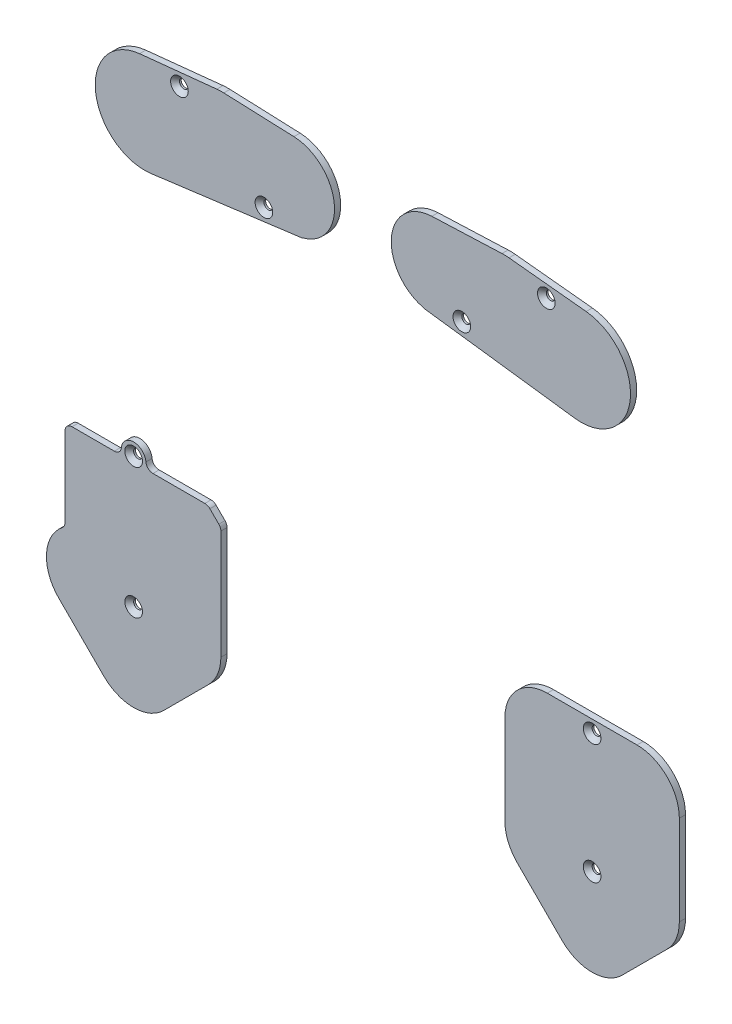
SolidWorks part; units mm, degrees
ref_plane "Front Plane" through (0, 0, 0) normal (0, 0, 1) x (1, 0, 0)
ref_plane "Top Plane" through (0, 0, 0) normal (0, 1, 0) x (1, 0, 0)
ref_plane "Right Plane" through (0, 0, 0) normal (1, 0, 0) x (0, 0, -1)
sketch "Sketch1" plane through (0, 0, 0) normal (0, 0, 1) x (1, 0, 0)
  line L0 (-43.969, -24.5) -> (-40.2721, -28.1969)
  line L2 (-40.2721, -28.1969) -> (-40.2721, -60)
  line L5 (63.3122, 76.6851) -> (41.4267, 78.9271)
  line L6 (39.439, 78.9888) -> (19.5552, 78.1913)
  line L7 (89.7279, -60) -> (89.7279, -34.5442)
  line L8 (77.7279, -22.5442) -> (52.2721, -22.5442)
  line L9 (40.2721, -34.5442) -> (40.2721, -60)
  line L10 (43.7868, -68.4853) -> (56.5147, -81.2132)
  line L11 (73.4853, -81.2132) -> (86.2132, -68.4853)
  line L12 (89.7279, -60) -> (89.7279, -34.5442)
  line L13 (-70.4772, -24.5) -> (-82.469, -24.5)
  line L14 (-84.469, -26.5) -> (-84.469, -49.0641)
  line L15 (-86.2132, -68.4853) -> (-73.4853, -81.2132)
  line L16 (-56.5147, -81.2132) -> (-43.7868, -68.4853)
  line L17 (-40.2721, -60) -> (-40.2721, -50)
  line L18 (-40.2721, -50) -> (-42.2721, -50)
  line L19 (-42.2721, -50) -> (-42.2721, -60)
  line L20 (-45.201, -67.0711) -> (-57.9289, -79.799)
  line L21 (-72.0711, -79.799) -> (-84.799, -67.0711)
  line L22 (-82.469, -51.1953) -> (-82.469, -26.5)
  line L23 (-82.469, -26.5) -> (-43.969, -26.5)
  line L24 (-43.969, -26.5) -> (-43.969, -24.5)
  line L25 (-43.969, -24.5) -> (-59.5228, -24.5)
  line L26 (-70.4772, -24.5) -> (-82.469, -24.5)
  line L27 (-84.469, -26.5) -> (-84.469, -49.0641)
  line L28 (-86.2132, -68.4853) -> (-73.4853, -81.2132)
  line L29 (-56.5147, -81.2132) -> (-43.7868, -68.4853)
  line L38 (-43.969, -24.5) -> (-59.5228, -24.5)
  line L39 (77.7279, -22.5442) -> (52.2721, -22.5442)
  line L40 (40.2721, -34.5442) -> (40.2721, -60)
  line L41 (43.7868, -68.4853) -> (56.5147, -81.2132)
  line L42 (73.4853, -81.2132) -> (86.2132, -68.4853)
  line L43 (17.3834, 54.4454) -> (60.0743, 48.8756)
  line L44 (63.3122, 76.6851) -> (41.4267, 78.9271)
  line L45 (39.439, 78.9888) -> (19.5552, 78.1913)
  line L46 (17.3834, 54.4454) -> (60.0743, 48.8756)
  line L47 (-41.4267, 78.9271) -> (-63.3122, 76.6851)
  line L48 (-60.0743, 48.8756) -> (-17.3834, 54.4454)
  line L49 (-19.5552, 78.1913) -> (-39.439, 78.9888)
  line L50 (-41.4267, 78.9271) -> (-63.3122, 76.6851)
  line L51 (-60.0743, 48.8756) -> (-17.3834, 54.4454)
  line L52 (-19.5552, 78.1913) -> (-39.439, 78.9888)
  circle A0 centre (-52.0128, 74.3243) radius 1.5 construction
  circle A1 centre (-52.0128, 74.3243) radius 1.5
  circle A2 centre (-28.0593, 56.5822) radius 1.5 construction
  circle A3 centre (-28.0593, 56.5822) radius 1.5
  arc A4 (60.0743, 48.8756) -> (63.3122, 76.6851) centre (61.8855, 62.758) ccw
  arc A5 (86.2132, -68.4853) -> (89.7279, -60) centre (77.7279, -60) ccw
  arc A6 (89.7279, -34.5442) -> (77.7279, -22.5442) centre (77.7279, -34.5442) ccw
  arc A7 (52.2721, -22.5442) -> (40.2721, -34.5442) centre (52.2721, -34.5442) ccw
  arc A8 (40.2721, -60) -> (43.7868, -68.4853) centre (52.2721, -60) ccw
  arc A9 (56.5147, -81.2132) -> (73.4853, -81.2132) centre (65, -72.7279) ccw
  arc A10 (86.2132, -68.4853) -> (89.7279, -60) centre (77.7279, -60) ccw
  arc A11 (-82.469, -24.5) -> (-84.469, -26.5) centre (-82.469, -26.5) ccw
  arc A12 (-85.2203, -50.6264) -> (-84.469, -49.0641) centre (-86.469, -49.0641) ccw
  arc A13 (-85.2203, -50.6264) -> (-86.2132, -68.4853) centre (-77.7279, -60) ccw
  arc A14 (-73.4853, -81.2132) -> (-56.5147, -81.2132) centre (-65, -72.7279) ccw
  arc A15 (-43.7868, -68.4853) -> (-40.2721, -60) centre (-52.2721, -60) ccw
  arc A16 (-45.201, -67.0711) -> (-42.2721, -60) centre (-52.2721, -60) ccw
  arc A17 (-72.0711, -79.799) -> (-57.9289, -79.799) centre (-65, -72.7279) ccw
  arc A18 (-82.469, -51.1953) -> (-84.799, -67.0711) centre (-77.7279, -60) ccw
  arc A19 (-61.5145, -22.6818) -> (-59.5228, -24.5) centre (-59.5228, -22.5) ccw
  arc A20 (-61.5145, -22.6818) -> (-68.4855, -22.6818) centre (-65, -23) ccw
  arc A21 (-70.4772, -24.5) -> (-68.4855, -22.6818) centre (-70.4772, -22.5) ccw
  arc A22 (-82.469, -24.5) -> (-84.469, -26.5) centre (-82.469, -26.5) ccw
  arc A23 (-85.2203, -50.6264) -> (-84.469, -49.0641) centre (-86.469, -49.0641) ccw
  arc A24 (-85.2203, -50.6264) -> (-86.2132, -68.4853) centre (-77.7279, -60) ccw
  arc A25 (-73.4853, -81.2132) -> (-56.5147, -81.2132) centre (-65, -72.7279) ccw
  arc A26 (-43.7868, -68.4853) -> (-40.2721, -60) centre (-52.2721, -60) ccw
  arc A30 (-61.5145, -22.6818) -> (-59.5228, -24.5) centre (-59.5228, -22.5) ccw
  arc A31 (-61.5145, -22.6818) -> (-68.4855, -22.6818) centre (-65, -23) ccw
  arc A32 (-70.4772, -24.5) -> (-68.4855, -22.6818) centre (-70.4772, -22.5) ccw
  arc A33 (89.7279, -34.5442) -> (77.7279, -22.5442) centre (77.7279, -34.5442) ccw
  arc A34 (52.2721, -22.5442) -> (40.2721, -34.5442) centre (52.2721, -34.5442) ccw
  arc A35 (40.2721, -60) -> (43.7868, -68.4853) centre (52.2721, -60) ccw
  arc A36 (56.5147, -81.2132) -> (73.4853, -81.2132) centre (65, -72.7279) ccw
  arc A37 (41.4267, 78.9271) -> (39.439, 78.9888) centre (40, 65) ccw
  arc A38 (19.5552, 78.1913) -> (16.9911, 54.5937) centre (20.0361, 66.201) ccw
  arc A39 (17.3834, 54.4454) -> (16.9911, 54.5937) centre (16.4837, 52.6592) ccw
  arc A40 (60.0743, 48.8756) -> (63.3122, 76.6851) centre (61.8855, 62.758) ccw
  arc A41 (41.4267, 78.9271) -> (39.439, 78.9888) centre (40, 65) ccw
  arc A42 (19.5552, 78.1913) -> (16.9911, 54.5937) centre (20.0361, 66.201) ccw
  arc A43 (17.3834, 54.4454) -> (16.9911, 54.5937) centre (16.4837, 52.6592) ccw
  arc A44 (-39.439, 78.9888) -> (-41.4267, 78.9271) centre (-40, 65) ccw
  arc A45 (-63.3122, 76.6851) -> (-60.0743, 48.8756) centre (-61.8855, 62.758) ccw
  arc A46 (-16.9911, 54.5937) -> (-17.3834, 54.4454) centre (-16.4837, 52.6592) ccw
  arc A47 (-16.9911, 54.5937) -> (-19.5552, 78.1913) centre (-20.0361, 66.201) ccw
  arc A48 (-39.439, 78.9888) -> (-41.4267, 78.9271) centre (-40, 65) ccw
  arc A49 (-63.3122, 76.6851) -> (-60.0743, 48.8756) centre (-61.8855, 62.758) ccw
  arc A50 (-16.9911, 54.5937) -> (-17.3834, 54.4454) centre (-16.4837, 52.6592) ccw
  arc A51 (-16.9911, 54.5937) -> (-19.5552, 78.1913) centre (-20.0361, 66.201) ccw
  circle A52 centre (52.0128, 74.3243) radius 1.5 construction
  circle A53 centre (52.0128, 74.3243) radius 1.5
  circle A54 centre (28.0593, 56.5822) radius 1.5 construction
  circle A55 centre (28.0593, 56.5822) radius 1.5
  circle A56 centre (65, -26.0442) radius 1.5 construction
  circle A57 centre (65, -26.0442) radius 1.5
  circle A58 centre (65, -60) radius 1.5 construction
  circle A59 centre (65, -60) radius 1.5
  circle A60 centre (-65, -23) radius 1.5 construction
  circle A61 centre (-65, -23) radius 1.5
  circle A62 centre (-65, -60) radius 1.5 construction
  circle A63 centre (-65, -60) radius 1.5
  circle A64 centre (-65, -60) radius 1.25
  circle A65 centre (-65, -23) radius 1.25
  circle A66 centre (65, -60) radius 1.25
  circle A67 centre (65, -26.0442) radius 1.25
  circle A68 centre (52.0128, 74.3243) radius 1.25
  circle A69 centre (28.0593, 56.5822) radius 1.25
  circle A70 centre (-28.0593, 56.5822) radius 1.25
  circle A71 centre (-52.0128, 74.3243) radius 1.25
  dimension "D6" = 2.5
  dimension "D2" = 135
  dimension "D1" = 0
  dimension "D3" = 0
  dimension "D4" = 0
  dimension "D5" = 0
extrude "Boss-Extrude1" add sketch "Sketch1" along normal blind 1.75 contours L2 A26 L29 A25 L28 A24 A23 L27 A22 L26 A32 A31 A30 L38 L0 | A65 | A64 | L42 A10 L12 A33 L39 A34 L40 A35 L41 A36 | A66 | A67 | A40 L44 A41 L45 A42 A43 L46 | A68 | A69 | L51 A50 A51 L52 A48 L50 A49 | A70 | A71
hole_wizard "CSK for M2.5 Flat Head Machine Screw1" positions "Sketch2" profile "Sketch3" countersink size "M2.5" standard "ANSI Metric" end condition through all
sketch "Sketch2" plane through (0, 0, 1.75) normal (0, 0, 1) x (1, 0, 0)
  point P0 (-65, -23)
  point P3 (-65, -60)
  point P6 (-52.0128, 74.3243)
  point P9 (-28.0593, 56.5822)
  point P12 (52.0128, 74.3243)
  point P15 (28.0593, 56.5822)
  point P18 (65, -26.0442)
  point P21 (65, -60)
sketch "Sketch3" plane through (-65, -23, 1.75) normal (1, 0, 0) x (0, -1, 0)
  line L0 (0, 0) -> (0, 1.75)
  line L1 (0, 1.75) -> (1.25, 1.75)
  line L2 (1.25, 1.75) -> (1.25, 1.25)
  line L3 (1.25, 1.25) -> (2.5, 0)
  line L5 (2.5, 0) -> (0, 0)
  line L6 (-1.25, 1.25) -> (-2.5, 0) construction
  line L11 (0, -6.35) -> (0, 107.95) construction
  dimension "Thru Hole Dia." = 2.5
  dimension "Thru Hole Depth" = 1.75
  dimension "Near C'Sink Dia." = 5
  dimension "Near C'Sink Angle" = 90
fillet "Fillet1" radius 2 2 edges at (-40.2721, -28.1969, 0.875) (-43.969, -24.5, 0.875)
